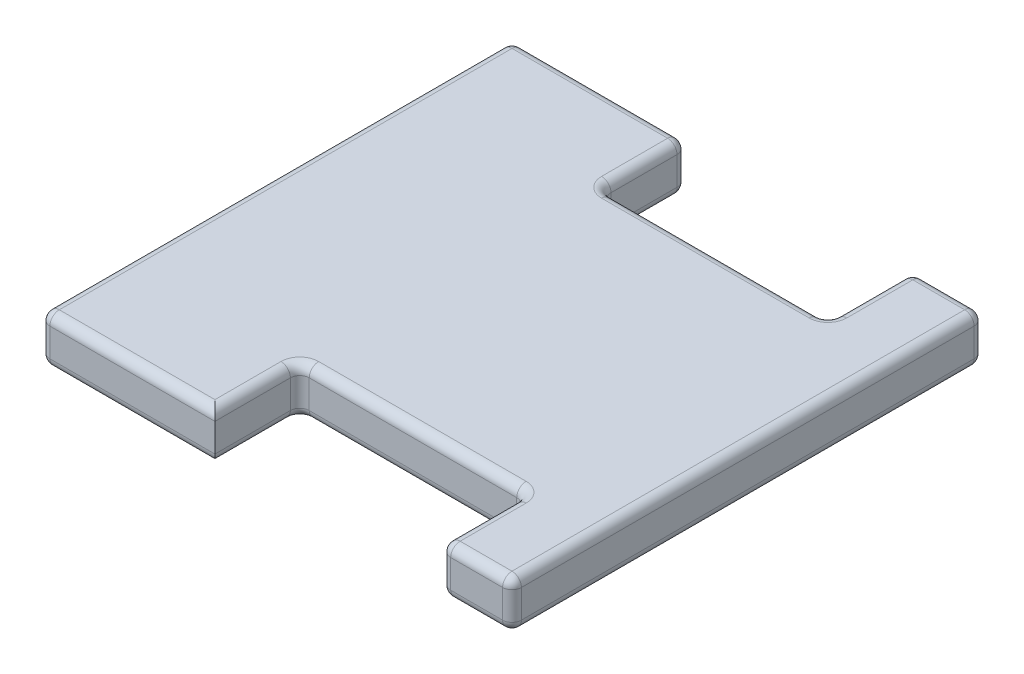
SolidWorks part; units mm, degrees
ref_plane "Front Plane" through (0, 0, 0) normal (0, 0, 1) x (1, 0, 0)
ref_plane "Top Plane" through (0, 0, 0) normal (0, 1, 0) x (1, 0, 0)
ref_plane "Right Plane" through (0, 0, 0) normal (1, 0, 0) x (0, 0, -1)
sketch "Sketch1" plane through (0, 0, 0) normal (0, 1, 0) x (1, 0, 0)
  line L0 (-123.8443, 0) -> (135.5231, 0) construction
  line L1 (100, -50) -> (100, 50)
  line L2 (100, 50) -> (85, 50)
  line L3 (85, 50) -> (85, 32)
  line L4 (85, 32) -> (37, 32)
  line L5 (37, 32) -> (37, 50)
  line L6 (37, 50) -> (0, 50)
  line L7 (0, 50) -> (0, -50)
  line L8 (100, -50) -> (85, -50)
  line L9 (85, -50) -> (85, -32)
  line L10 (85, -32) -> (37, -32)
  line L11 (37, -32) -> (37, -50)
  line L12 (37, -50) -> (0, -50)
  point P12 (100, 0)
  point P17 (0, 0)
  dimension "D1" = 50
  dimension "D2" = 15
  dimension "D3" = 48
  dimension "D4" = 18
  dimension "D5" = 37
  dimension "D6" = 50
extrude "Boss-Extrude1" add sketch "Sketch1" along normal blind 10
fillet "Fillet1" radius 2 35 edges at (37, 10, 41) (37, 0, 41) (85, 10, 41) (85, 0, 41) (85, 5, 50) (92.5, 10, 50) (100, 5, 50) (92.5, 0, 50) (85, 10, -41) (85, 5, -32) (85, 0, -41) (37, 5, 32) (61, 10, 32) (85, 5, 32) (61, 0, 32) (100, 5, -50) (92.5, 10, -50) (85, 5, -50) (92.5, 0, -50) (37, 5, -50) (18.5, 10, -50) (0, 5, -50) (18.5, 0, -50) (100, 0, 0) (100, 10, 0) (37, 5, -32) (61, 0, -32) (61, 10, -32) (37, 0, -41) (37, 10, -41) (0, 0, 0) (0, 10, 0) (0, 5, 50) (18.5, 0, 50) (18.5, 10, 50)
ref_plane "Plane1" through (83, 8, -32) normal (1, 0, 0) x (0, 0, -1)
equation "\"ๅ\"=10"
